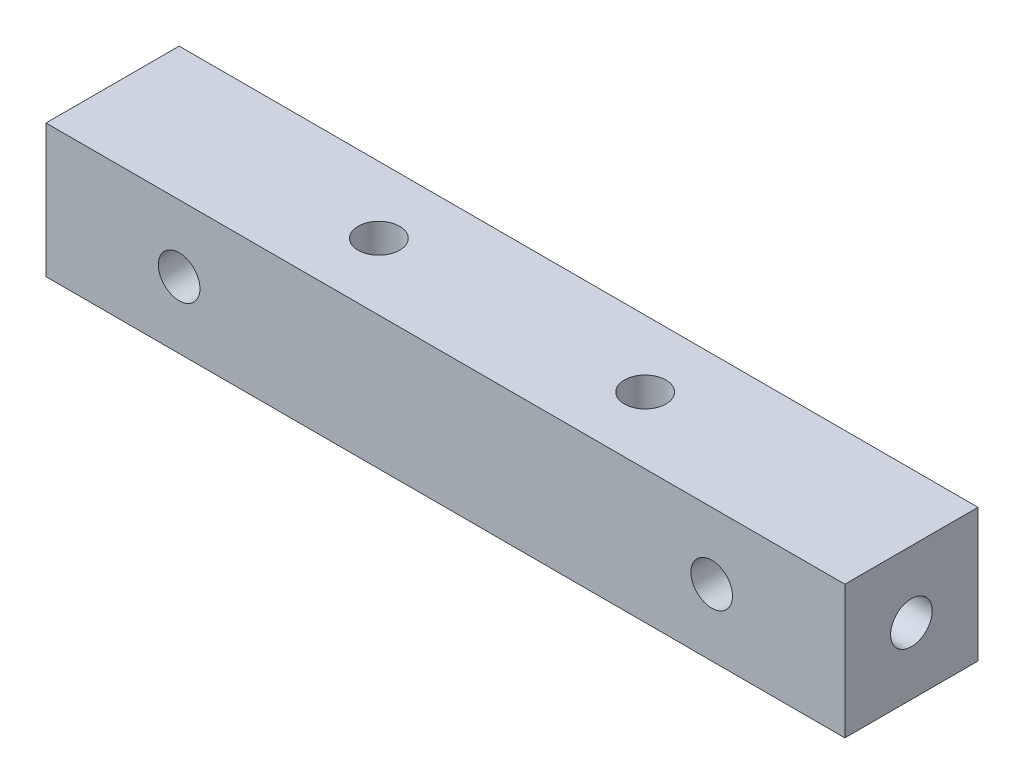
SolidWorks part; units mm, degrees
material "6060 合金"
ref_plane "前视基准面" through (0, 0, 0) normal (0, 0, 1) x (1, 0, 0)
ref_plane "上视基准面" through (0, 0, 0) normal (0, 1, 0) x (1, 0, 0)
ref_plane "右视基准面" through (0, 0, 0) normal (1, 0, 0) x (0, 0, -1)
sketch "草图1" plane through (0, 0, 0) normal (0, 0, 1) x (1, 0, 0)
  line L1 (-24, 4) -> (24, 4)
  line L2 (-24, 4) -> (-24, -4)
  line L3 (-24, -4) -> (24, -4)
  line L4 (24, 4) -> (24, -4)
  line L5 (-24, 4) -> (24, -4) construction
  line L6 (-24, -4) -> (24, 4) construction
  point P0 (0, 0)
  dimension "D1" = 8
  dimension "D2" = 48
extrude "凸台-拉伸1" add sketch "草图1" along normal blind 8
hole_wizard "M3 螺纹孔1" positions "草图2" profile "草图3" tap size "M3" standard "GB"
sketch "草图2" plane through (0, 0, 8) normal (0, 0, 1) x (1, 0, 0)
  point P0 (-16, 0)
  point P2 (16, 0)
  dimension "D1" = 16
  dimension "D2" = 16
sketch "草图3" plane through (-16, 0, 8) normal (1, 0, 0) x (0, -1, 0)
  line L0 (0, 0) -> (0, 19.2511)
  line L1 (0, 19.2511) -> (1.25, 18.5)
  line L2 (1.25, 18.5) -> (1.25, 0)
  line L5 (1.25, 0) -> (0, 0)
  line L10 (0, 19.2511) -> (-1.25, 18.5) construction
  line L11 (0, -6.35) -> (0, 107.95) construction
  dimension "螺纹孔钻头直径" = 2.5
  dimension "螺纹孔钻头深度" = 18.5
  dimension "导头角度" = 118
cosmetic thread "孔螺蚊线1"
cosmetic thread "孔螺蚊线2"
hole_wizard "M3 螺纹孔2" positions "草图4" profile "草图5" tap size "M3" standard "GB"
sketch "草图4" plane through (0, 4, 0) normal (0, 1, 0) x (1, 0, 0)
  point P0 (-8, -4)
  point P2 (8, -4)
  dimension "D1" = 8
  dimension "D2" = 8
  dimension "D3" = 4
  dimension "D4" = 4
sketch "草图5" plane through (-8, 4, 4) normal (1, 0, 0) x (0, 0, 1)
  line L0 (0, 0) -> (0, 19.2511)
  line L1 (0, 19.2511) -> (1.25, 18.5)
  line L2 (1.25, 18.5) -> (1.25, 0)
  line L5 (1.25, 0) -> (0, 0)
  line L10 (0, 19.2511) -> (-1.25, 18.5) construction
  line L11 (0, -6.35) -> (0, 107.95) construction
  dimension "螺纹孔钻头直径" = 2.5
  dimension "螺纹孔钻头深度" = 18.5
  dimension "导头角度" = 118
cosmetic thread "孔螺蚊线3"
cosmetic thread "孔螺蚊线4"
hole_wizard "M3 螺纹孔3" positions "草图7" profile "草图8" tap size "M3" standard "GB"
sketch "草图7" plane through (-24, 0, 0) normal (-1, 0, 0) x (0, 0, 1)
  point P0 (4, 0)
  dimension "D1" = 4
sketch "草图8" plane through (-24, 0, 4) normal (0, 1, 0) x (0, 0, 1)
  line L0 (0, 0) -> (0, 59.2511)
  line L1 (0, 59.2511) -> (1.25, 58.5)
  line L2 (1.25, 58.5) -> (1.25, 0)
  line L5 (1.25, 0) -> (0, 0)
  line L10 (0, 59.2511) -> (-1.25, 58.5) construction
  line L11 (0, -6.35) -> (0, 107.95) construction
  dimension "螺纹孔钻头直径" = 2.5
  dimension "螺纹孔钻头深度" = 58.5
  dimension "导头角度" = 118
cosmetic thread "孔螺蚊线5"
